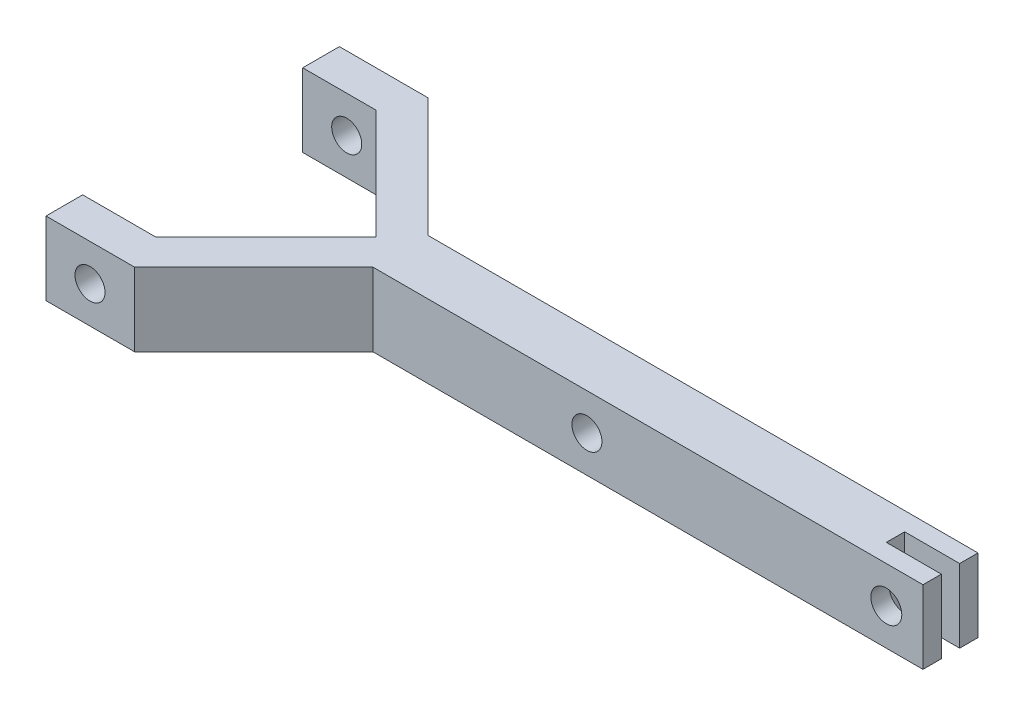
SolidWorks part; units mm, degrees
ref_plane "Front" through (0, 0, 0) normal (0, 0, 1) x (1, 0, 0)
ref_plane "Top" through (0, 0, 0) normal (0, 1, 0) x (1, 0, 0)
ref_plane "Right" through (0, 0, 0) normal (1, 0, 0) x (0, 0, -1)
sketch "Esquisse1" plane through (0, 0, 0) normal (0, 0, 1) x (1, 0, 0)
  line L1 (-6.35, 6.35) -> (6.35, 6.35)
  line L2 (-6.35, 6.35) -> (-6.35, -6.35)
  line L3 (-6.35, -6.35) -> (6.35, -6.35)
  line L4 (6.35, 6.35) -> (6.35, -6.35)
  line L5 (-6.35, 6.35) -> (6.35, -6.35) construction
  line L6 (-6.35, -6.35) -> (6.35, 6.35) construction
  point P0 (0, 0)
  dimension "D1" = 12.7
  dimension "D2" = 12.7
extrude "Boss.-Extru.1" add sketch "Esquisse1" along normal mid plane 9.525
sketch "Esquisse2" plane through (0, 0, 4.7625) normal (0, 0, 1) x (1, 0, 0)
  circle A0 centre (0, 0) radius 2.6
  dimension "D1" = 5.2
extrude "Enlèv. mat.-Extru.1" cut sketch "Esquisse2" against normal through all
sketch "Esquisse4" plane through (6.35, 0, 0) normal (1, 0, 0) x (0, 0, -1)
  line L1 (-4.7625, 6.35) -> (4.7625, 6.35)
  line L2 (-4.7625, 6.35) -> (-4.7625, -6.35)
  line L3 (-4.7625, -6.35) -> (4.7625, -6.35)
  line L4 (4.7625, 6.35) -> (4.7625, -6.35)
  line L5 (-4.7625, 6.35) -> (4.7625, -6.35) construction
  line L6 (-4.7625, -6.35) -> (4.7625, 6.35) construction
  point P0 (-4.7289, 6.3027)
extrude "Boss.-Extru.3" add sketch "Esquisse4" along normal blind 51.8414
sketch "Esquisse5" plane through (0, 0, 4.7625) normal (0, 0, 1) x (1, 0, 0)
  line L0 (58.1914, 6.35) -> (58.1914, -6.35) construction
  line L1 (-6.35, -6.35) -> (58.1914, -6.35) construction
  circle A0 centre (51.8414, 0) radius 2.6797
  point P2 (0, 0)
  dimension "D1" = 5.3594
  dimension "D2" = 6.35
  dimension "D3" = 6.35
extrude "Enlèv. mat.-Extru.2" cut sketch "Esquisse5" against normal through all
sketch "Esquisse6" plane through (0, 6.35, 0) normal (0, 1, 0) x (1, 0, 0)
  line L0 (58.1914, 4.7625) -> (58.1914, -4.7625) construction
  line L1 (58.1914, 1.5875) -> (48.6664, 1.5875)
  line L2 (58.1914, 1.5875) -> (58.1914, -1.5875)
  line L3 (58.1914, -1.5875) -> (48.6664, -1.5875)
  line L4 (48.6664, 1.5875) -> (48.6664, -1.5875)
  line L5 (58.1914, 4.7625) -> (-6.35, 4.7625) construction
  line L6 (58.1914, -4.7625) -> (-6.35, -4.7625) construction
  dimension "D1" = 3.175
  dimension "D2" = 3.175
  dimension "D3" = 9.525
extrude "Enlèv. mat.-Extru.3" cut sketch "Esquisse6" against normal through all
sketch "Esquisse7" plane through (-6.35, 0, 0) normal (-1, 0, 0) x (0, 0, 1)
  line L1 (-4.7625, 6.35) -> (4.7625, 6.35)
  line L2 (-4.7625, 6.35) -> (-4.7625, -6.35)
  line L3 (-4.7625, -6.35) -> (4.7625, -6.35)
  line L4 (4.7625, 6.35) -> (4.7625, -6.35)
extrude "Boss.-Extru.4" add sketch "Esquisse7" along normal blind 34.925
sketch "Esquisse8" plane through (0, 6.35, 0) normal (0, 1, 0) x (1, 0, 0)
  line L0 (-37.0572, 4.7625) -> (-57.6947, 25.4)
  line L1 (-57.6947, 25.4) -> (-73.025, 25.4)
  line L2 (-73.025, 25.4) -> (-73.025, 19.05)
  line L3 (-73.025, 19.05) -> (-60.325, 19.05)
  line L4 (-60.325, 19.05) -> (-41.275, 0)
  line L5 (-41.275, -4.7625) -> (-41.275, 4.7625) construction
  line L6 (-41.275, 0) -> (-60.325, -19.05)
  line L7 (-60.325, -19.05) -> (-73.025, -19.05)
  line L8 (-73.025, -19.05) -> (-73.025, -25.4)
  line L9 (-73.025, -25.4) -> (-57.6947, -25.4)
  line L10 (-57.6947, -25.4) -> (-37.0572, -4.7625)
  line L11 (58.1914, -4.7625) -> (-41.275, -4.7625) construction
  line L12 (58.1914, 4.7625) -> (-41.275, 4.7625) construction
  line L13 (-41.275, 0) -> (-91.3633, 0) construction
  line L14 (-37.0572, -4.7625) -> (-37.0572, 4.7625)
  dimension "D1" = 6.35
  dimension "D2" = 6.35
  dimension "D3" = 6.35
  dimension "D4" = 6.35
  dimension "D5" = 38.1
  dimension "D6" = 19.05
  dimension "D7" = 12.7
  dimension "D8" = 19.05
  dimension "D9" = 19.05
extrude "Boss.-Extru.5" add sketch "Esquisse8" against normal blind 12.7
sketch "Esquisse9" plane through (0, 0, 25.4) normal (0, 0, 1) x (1, 0, 0)
  line L0 (-73.025, 6.35) -> (-57.6947, 6.35) construction
  line L1 (-73.025, -6.35) -> (-73.025, 6.35) construction
  circle A0 centre (-65.405, 0) radius 2.6
  dimension "D1" = 5.2
  dimension "D2" = 6.35
  dimension "D3" = 7.62
extrude "Enlèv. mat.-Extru.4" cut sketch "Esquisse9" against normal through all
